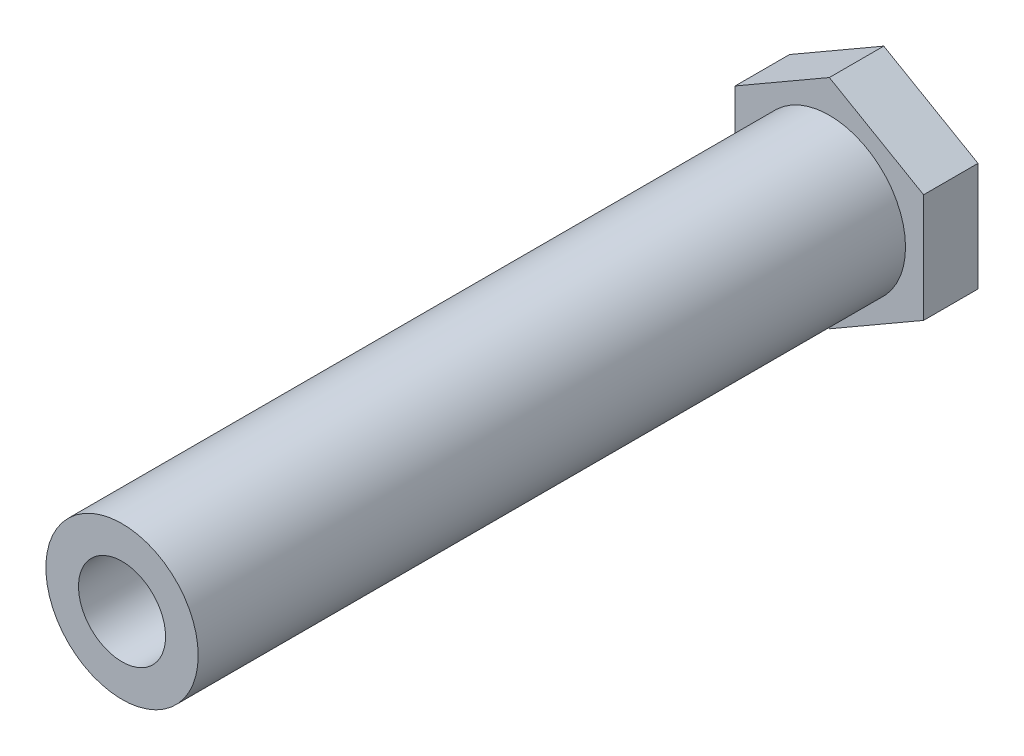
SolidWorks part; units mm, degrees
material "Alumina"
ref_plane "Front Plane" through (0, 0, 0) normal (0, 0, 1) x (1, 0, 0)
ref_plane "Top Plane" through (0, 0, 0) normal (0, 1, 0) x (1, 0, 0)
ref_plane "Right Plane" through (0, 0, 0) normal (1, 0, 0) x (0, 0, -1)
sketch "Sketch1" plane through (0, 0, 0) normal (0, 0, 1) x (1, 0, 0)
  line L1 (0, 10) -> (-8.6603, 5)
  line L2 (-8.6603, 5) -> (-8.6603, -5)
  line L3 (-8.6603, -5) -> (0, -10)
  line L4 (0, -10) -> (8.6603, -5)
  line L5 (8.6603, -5) -> (8.6603, 5)
  line L6 (8.6603, 5) -> (0, 10)
  circle A0 centre (0, 0) radius 10
  circle A1 centre (0, 0) radius 8.6603 construction
  dimension "D1" = 20
extrude "Boss-Extrude1" add sketch "Sketch1" along normal blind 5 contours L5 L6 L1 L2 L3 L4
sketch "Sketch2" plane through (0, 0, 5) normal (0, 0, 1) x (1, 0, 0)
  circle A0 centre (0, 0) radius 7
  dimension "D1" = 14
extrude "Boss-Extrude2" add sketch "Sketch2" along normal blind 65
sketch "Sketch3" plane through (0, 0, 70) normal (0, 0, 1) x (1, 0, 0)
  circle A0 centre (0, 0) radius 4
  dimension "D1" = 8
extrude "Cut-Extrude1" cut sketch "Sketch3" against normal blind 20
